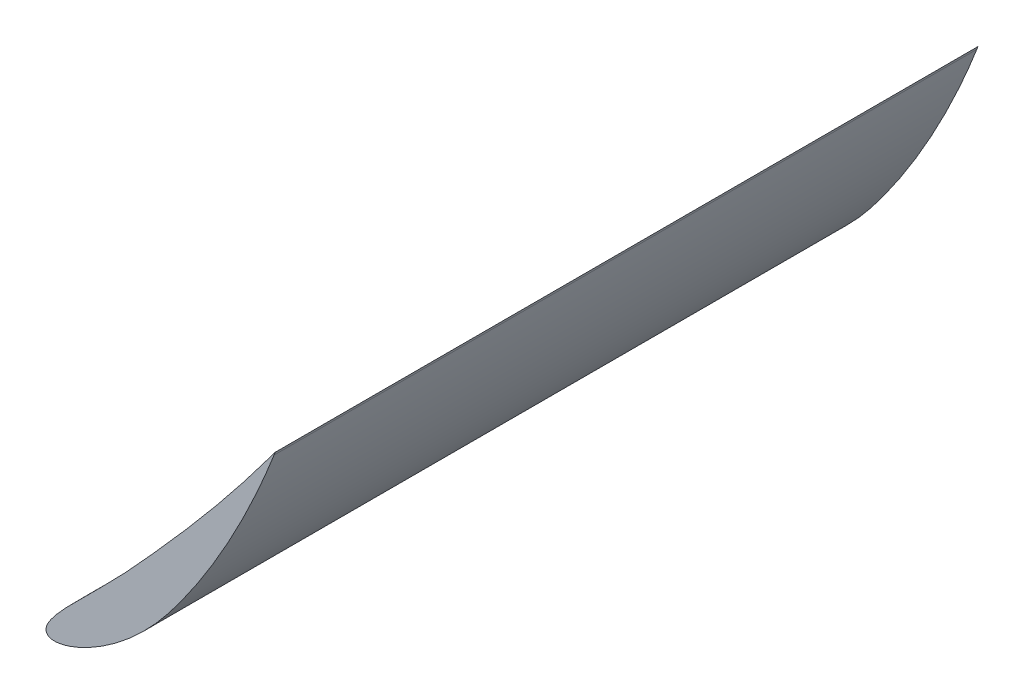
SolidWorks part; units mm, degrees
ref_plane "Front Plane" through (0, 0, 0) normal (0, 0, 1) x (1, 0, 0)
ref_plane "Top Plane" through (0, 0, 0) normal (0, 1, 0) x (1, 0, 0)
ref_plane "Right Plane" through (0, 0, 0) normal (1, 0, 0) x (0, 0, -1)
sketch "Sketch1" plane through (0, 0, 0) normal (0, 0, 1) x (1, 0, 0)
  line L12 (81.634, 97.2876) -> (0, 0) construction
  line L13 (81.5114, 97.3905) -> (81.7566, 97.1848) construction
  line L15 (0, 0) -> (49.9996, 0) construction
  line L16 (81.5114, 97.3905) -> (82.1927, 98.3086)
  line L17 (81.7566, 97.1848) -> (82.1927, 98.3086)
  spline S1 degree 3 poles (81.7566, 97.1848) (81.7317, 97.1205) (81.6321, 96.864) (81.4077, 96.2892) (81.0334, 95.3367) (80.5075, 94.0156) (79.829, 92.3376) (78.9965, 90.3178) (78.0086, 87.974) (76.8643, 85.3265) (75.5632, 82.3981) (74.105, 79.2134) (72.4912, 75.7986) (70.7234, 72.1816) (68.8046, 68.3914) (66.7394, 64.4574) (64.5329, 60.4101) (62.192, 56.2804) (59.7244, 52.0991) (57.1391, 47.8973) (54.4471, 43.705) (51.6593, 39.5528) (48.7894, 35.4693) (45.8491, 31.4847) (42.8637, 27.6176) (39.7792, 23.949) (36.6227, 20.4984) (33.4183, 17.2831) (30.1932, 14.317) (26.9767, 11.6105) (23.7993, 9.1714) (20.6932, 7.004) (17.6904, 5.1108) (14.8237, 3.491) (12.1246, 2.1423) (9.6232, 1.0613) (7.3474, 0.2422) (5.3215, -0.3201) (3.5651, -0.6329) (2.09, -0.7009) (0.8965, -0.5251) (-0.0134, -0.0818) (-0.579, 0.6607) (-0.6886, 1.6321) (-0.4133, 2.7429) (0.1968, 4.0285) (1.138, 5.5031) (2.4006, 7.1704) (3.9718, 9.0291) (5.834, 11.0763) (7.9665, 13.3081) (10.3447, 15.7209) (12.9427, 18.3096) (15.7314, 21.0695) (18.6806, 23.9946) (21.7585, 27.0784) (24.933, 30.313) (28.1717, 33.6891) (31.4437, 37.1956) (34.7151, 40.8229) (38.0269, 44.4942) (41.3443, 48.201) (44.6452, 51.9215) (47.9049, 55.6368) (51.1016, 59.325) (54.2144, 62.9647) (57.224, 66.5334) (60.1133, 70.0079) (62.8659, 73.3655) (65.468, 76.5829) (67.9066, 79.6376) (70.1703, 82.5079) (72.2485, 85.1731) (74.1325, 87.6134) (75.814, 89.8111) (77.286, 91.7497) (78.542, 93.415) (79.577, 94.7947) (80.3867, 95.8784) (80.9673, 96.6583) (81.3169, 97.1284) (81.4725, 97.338) (81.5114, 97.3905) knots 0 0 0 0 0.000791 0.00316 0.007087 0.012544 0.019489 0.027873 0.037633 0.048699 0.060994 0.074433 0.088923 0.104368 0.120665 0.13771 0.155392 0.173601 0.192223 0.211146 0.230254 0.249435 0.268577 0.287568 0.306301 0.324671 0.342595 0.359992 0.376786 0.392898 0.408252 0.422771 0.43638 0.449003 0.46057 0.471014 0.48028 0.488325 0.495133 0.500728 0.505217 0.508863 0.51207 0.515471 0.519696 0.525078 0.53175 0.539754 0.54908 0.559692 0.571531 0.584528 0.598598 0.61365 0.629586 0.6463 0.663686 0.681632 0.700027 0.718761 0.737727 0.756809 0.775888 0.794846 0.813569 0.83194 0.849847 0.86718 0.883834 0.899707 0.914701 0.928723 0.941687 0.953513 0.964128 0.973465 0.981467 0.988083 0.993272 0.997002 0.999249 1 1 1 1
  point P10 (81.634, 97.2876)
  dimension "D1" = 50
  dimension "D2" = 127
extrude "Boss-Extrude1" add sketch "Sketch1" along normal blind 254
sketch "Sketch2" plane through (0, 0, 254) normal (0, 0, 1) x (1, 0, 0)
  line L0 (81.5114, 97.3905) -> (81.7566, 97.1848) construction
  line L1 (81.634, 97.2876) -> (0, 0) construction
  line L2 (81.7566, 97.1848) -> (82.1927, 98.3086)
  line L3 (82.1927, 98.3086) -> (81.5114, 97.3905)
  line L4 (81.7566, 97.1848) -> (82.1927, 98.3086) construction
  line L5 (82.1927, 98.3086) -> (81.5114, 97.3905) construction
  spline S1 degree 3 poles (2552.7951, -1600.9616) (120.8859, 159.412) (103.1981, 126.5505) (80.9673, 96.6583) (80.3867, 95.8784) (79.577, 94.7947) (78.542, 93.415) (77.286, 91.7497) (75.814, 89.8111) (74.1325, 87.6134) (72.2485, 85.1731) (70.1703, 82.5079) (67.9066, 79.6376) (65.468, 76.5829) (62.8659, 73.3655) (60.1133, 70.0079) (57.224, 66.5334) (54.2144, 62.9647) (51.1016, 59.325) (47.9049, 55.6368) (44.6452, 51.9215) (41.3443, 48.201) (38.0269, 44.4942) (34.7151, 40.8229) (31.4437, 37.1956) (28.1717, 33.6891) (24.933, 30.313) (21.7585, 27.0784) (18.6806, 23.9946) (15.7314, 21.0695) (12.9427, 18.3096) (10.3447, 15.7209) (7.9665, 13.3081) (5.834, 11.0763) (3.9718, 9.0291) (2.4006, 7.1704) (1.138, 5.5031) (0.1968, 4.0285) (-0.4133, 2.7429) (-0.6886, 1.6321) (-0.579, 0.6607) (-0.0134, -0.0818) (0.8965, -0.5251) (2.09, -0.7009) (3.5651, -0.6329) (5.3215, -0.3201) (7.3474, 0.2422) (9.6232, 1.0613) (12.1246, 2.1423) (14.8237, 3.491) (17.6904, 5.1108) (20.6932, 7.004) (23.7993, 9.1714) (26.9767, 11.6105) (30.1932, 14.317) (33.4183, 17.2831) (36.6227, 20.4984) (39.7792, 23.949) (42.8637, 27.6176) (45.8491, 31.4847) (48.7894, 35.4693) (51.6593, 39.5528) (54.4471, 43.705) (57.1391, 47.8973) (59.7244, 52.0991) (62.192, 56.2804) (64.5329, 60.4101) (66.7394, 64.4574) (68.8046, 68.3914) (70.7234, 72.1816) (72.4912, 75.7986) (74.105, 79.2134) (75.5632, 82.3981) (76.8643, 85.3265) (78.0086, 87.974) (78.9965, 90.3178) (79.829, 92.3376) (80.5075, 94.0156) (81.0334, 95.3367) (81.4077, 96.2892) (92.7855, 125.4365) (97.6499, 156.7488) (2908.7392, -903.0108) knots -0.421086 -0.421086 -0.421086 -0.421086 0.000751 0.002998 0.006728 0.011917 0.018533 0.026535 0.035872 0.046487 0.058313 0.071277 0.085299 0.100293 0.116166 0.13282 0.150153 0.16806 0.186431 0.205154 0.224112 0.243191 0.262273 0.281239 0.299973 0.318368 0.336314 0.3537 0.370414 0.38635 0.401402 0.415472 0.428469 0.440308 0.45092 0.460246 0.46825 0.474922 0.480304 0.484529 0.48793 0.491137 0.494783 0.499272 0.504867 0.511675 0.51972 0.528986 0.53943 0.550997 0.56362 0.577229 0.591748 0.607102 0.623214 0.640008 0.657405 0.675329 0.693699 0.712432 0.731423 0.750565 0.769746 0.788854 0.807777 0.826399 0.844608 0.86229 0.879335 0.895632 0.911077 0.925567 0.939006 0.951301 0.962367 0.972127 0.980511 0.987456 0.992913 0.99684 0.999209 1.352244 1.352244 1.352244 1.352244 only from (81.5114, 97.3905) to (81.7566, 97.1848)
  spline S2 degree 3 poles (81.5114, 97.3905) (81.4725, 97.338) (81.3169, 97.1284) (80.9673, 96.6583) (80.3867, 95.8784) (79.577, 94.7947) (78.542, 93.415) (77.286, 91.7497) (75.814, 89.8111) (74.1325, 87.6134) (72.2485, 85.1731) (70.1703, 82.5079) (67.9066, 79.6376) (65.468, 76.5829) (62.8659, 73.3655) (60.1133, 70.0079) (57.224, 66.5334) (54.2144, 62.9647) (51.1016, 59.325) (47.9049, 55.6368) (44.6452, 51.9215) (41.3443, 48.201) (38.0269, 44.4942) (34.7151, 40.8229) (31.4437, 37.1956) (28.1717, 33.6891) (24.933, 30.313) (21.7585, 27.0784) (18.6806, 23.9946) (15.7314, 21.0695) (12.9427, 18.3096) (10.3447, 15.7209) (7.9665, 13.3081) (5.834, 11.0763) (3.9718, 9.0291) (2.4006, 7.1704) (1.138, 5.5031) (0.1968, 4.0285) (-0.4133, 2.7429) (-0.6886, 1.6321) (-0.579, 0.6607) (-0.0134, -0.0818) (0.8965, -0.5251) (2.09, -0.7009) (3.5651, -0.6329) (5.3215, -0.3201) (7.3474, 0.2422) (9.6232, 1.0613) (12.1246, 2.1423) (14.8237, 3.491) (17.6904, 5.1108) (20.6932, 7.004) (23.7993, 9.1714) (26.9767, 11.6105) (30.1932, 14.317) (33.4183, 17.2831) (36.6227, 20.4984) (39.7792, 23.949) (42.8637, 27.6176) (45.8491, 31.4847) (48.7894, 35.4693) (51.6593, 39.5528) (54.4471, 43.705) (57.1391, 47.8973) (59.7244, 52.0991) (62.192, 56.2804) (64.5329, 60.4101) (66.7394, 64.4574) (68.8046, 68.3914) (70.7234, 72.1816) (72.4912, 75.7986) (74.105, 79.2134) (75.5632, 82.3981) (76.8643, 85.3265) (78.0086, 87.974) (78.9965, 90.3178) (79.829, 92.3376) (80.5075, 94.0156) (81.0334, 95.3367) (81.4077, 96.2892) (81.6321, 96.864) (81.7317, 97.1205) (81.7566, 97.1848) knots 0 0 0 0 0.000751 0.002998 0.006728 0.011917 0.018533 0.026535 0.035872 0.046487 0.058313 0.071277 0.085299 0.100293 0.116166 0.13282 0.150153 0.16806 0.186431 0.205154 0.224112 0.243191 0.262273 0.281239 0.299973 0.318368 0.336314 0.3537 0.370414 0.38635 0.401402 0.415472 0.428469 0.440308 0.45092 0.460246 0.46825 0.474922 0.480304 0.484529 0.48793 0.491137 0.494783 0.499272 0.504867 0.511675 0.51972 0.528986 0.53943 0.550997 0.56362 0.577229 0.591748 0.607102 0.623214 0.640008 0.657405 0.675329 0.693699 0.712432 0.731423 0.750565 0.769746 0.788854 0.807777 0.826399 0.844608 0.86229 0.879335 0.895632 0.911077 0.925567 0.939006 0.951301 0.962367 0.972127 0.980511 0.987456 0.992913 0.99684 0.999209 1 1 1 1 construction
  dimension "D1" = 0
